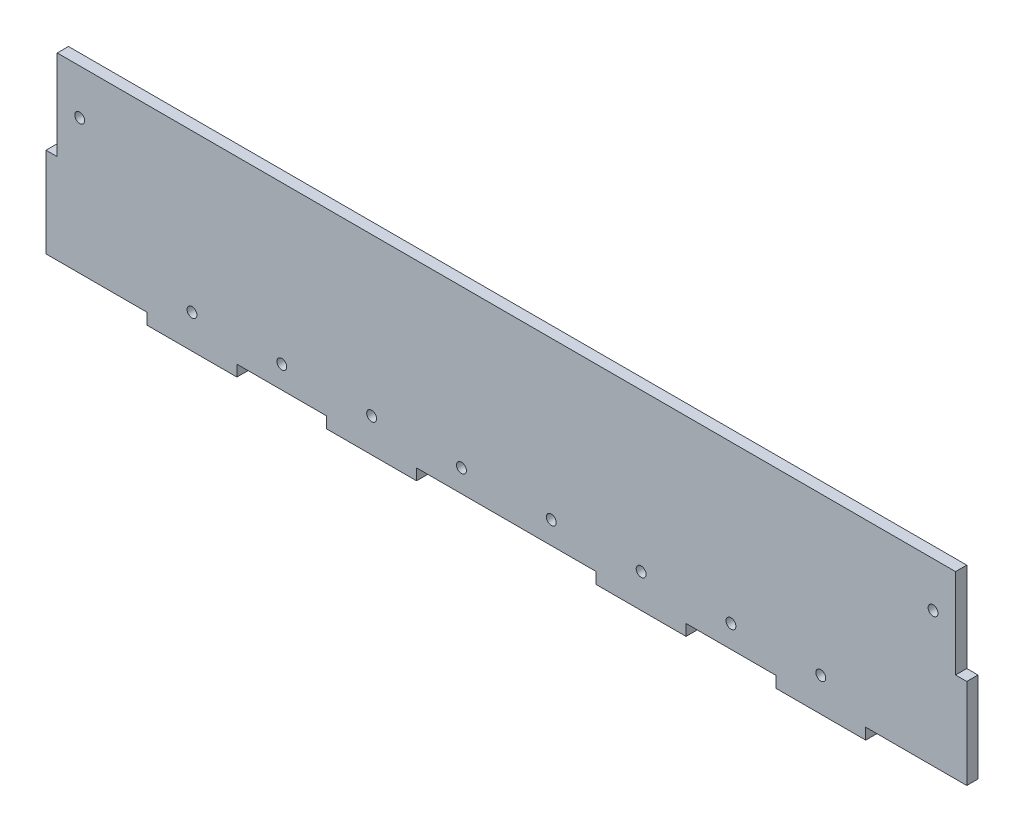
SolidWorks part; units mm, degrees
ref_plane "前视基准面" through (0, 0, 0) normal (0, 0, 1) x (1, 0, 0)
ref_plane "上视基准面" through (0, 0, 0) normal (0, 1, 0) x (1, 0, 0)
ref_plane "右视基准面" through (0, 0, 0) normal (1, 0, 0) x (0, 0, -1)
sketch "草图1" plane through (0, 0, 0) normal (0, 0, 1) x (1, 0, 0)
  line L2 (-200, 150) -> (200, 150)
  line L3 (200, -150) -> (200, -110)
  line L4 (-200, -150) -> (-200, -110)
  line L5 (-200, -150) -> (-160, -150)
  line L6 (-200, -150) -> (-160, -150)
  line L7 (-160, -150) -> (-160, -155)
  line L8 (-160, -155) -> (-120, -155)
  line L9 (-120, -155) -> (-120, -150)
  line L10 (-120, -150) -> (-80, -150)
  line L11 (-80, -150) -> (-80, -155)
  line L12 (-80, -155) -> (-40, -155)
  line L13 (-40, -155) -> (-40, -150)
  line L14 (-40, -150) -> (40, -150)
  line L15 (40, -150) -> (40, -155)
  line L16 (40, -155) -> (80, -155)
  line L17 (80, -155) -> (80, -150)
  line L18 (80, -150) -> (120, -150)
  line L19 (120, -150) -> (120, -155)
  line L20 (120, -155) -> (160, -155)
  line L21 (160, -155) -> (160, -150)
  line L22 (80, -150) -> (120, -150)
  line L23 (-120, -150) -> (-80, -150)
  line L24 (-40, -150) -> (40, -150)
  line L25 (160, -150) -> (200, -150)
  line L26 (-200, 110) -> (-200, 150)
  line L27 (-200, -70) -> (-200, -30)
  line L28 (-205, -30) -> (-205, 30)
  line L29 (-205, 30) -> (-200, 30)
  line L30 (-200, 30) -> (-200, 70)
  line L31 (-200, 70) -> (-205, 70)
  line L32 (-205, 70) -> (-205, 110)
  line L33 (-205, 110) -> (-200, 110)
  line L34 (-205, -30) -> (-200, -30)
  line L35 (-200, -70) -> (-205, -70)
  line L36 (-205, -70) -> (-205, -110)
  line L37 (-205, -110) -> (-200, -110)
  line L38 (-200, 30) -> (-200, 70)
  line L39 (200, 110) -> (200, 150)
  line L40 (205, -70) -> (205, -110)
  line L41 (205, -110) -> (200, -110)
  line L42 (200, -70) -> (205, -70)
  line L43 (205, -30) -> (200, -30)
  line L44 (205, -30) -> (205, 30)
  line L45 (205, 30) -> (200, 30)
  line L46 (200, 70) -> (205, 70)
  line L47 (205, 70) -> (205, 110)
  line L48 (205, 110) -> (200, 110)
  line L49 (200, 30) -> (200, 70)
  line L50 (200, -70) -> (200, -30)
  circle A0 centre (-140, -140) radius 2.2
  circle A1 centre (-100, -140) radius 2.2
  circle A2 centre (-60, -140) radius 2.2
  circle A3 centre (-20, -140) radius 2.2
  circle A4 centre (20, -140) radius 2.2
  circle A5 centre (60, -140) radius 2.2
  circle A6 centre (100, -140) radius 2.2
  circle A7 centre (140, -140) radius 2.2
  circle A8 centre (-190, 110) radius 2.2
  circle A9 centre (-190, 70) radius 2.2
  circle A10 centre (-190, 30) radius 2.2
  circle A11 centre (-190, -30) radius 2.2
  circle A12 centre (-190, -70) radius 2.2
  circle A13 centre (-190, -110) radius 2.2
  circle A14 centre (190, -110) radius 2.2
  circle A15 centre (190, -70) radius 2.2
  circle A16 centre (190, -30) radius 2.2
  circle A17 centre (190, 30) radius 2.2
  circle A18 centre (190, 70) radius 2.2
  circle A19 centre (190, 110) radius 2.2
extrude "凸台-拉伸1" add sketch "草图1" along normal blind 5 contours L42 L50 L43 L44 L45 L49 L46 L47 L48 L39 L2 L26 L33 L32 L31 L30 L29 L28 L34 L27 L35 L36 L37 L4 L5 L7 L8 L9 L10 L11 L12 L13 L14 L15 L16 L17 L18 L19 L20 L21 L25 L3 L41 L40 A18 A16 A14
sketch "草图2" plane through (0, 0, 5) normal (0, 0, 1) x (1, 0, 0)
  line L0 (-205, 110) -> (-200, 110)
  line L1 (-205, 110) -> (-205, -110.2824)
  line L2 (-200, 110) -> (-200, -110.2824)
  line L3 (-205, -110.2824) -> (-200, -110.2824)
  line L4 (200, 110) -> (205, 110)
  line L5 (200, 110) -> (200, -109.8687)
  line L6 (205, 110) -> (205, -109.8687)
  line L7 (200, -109.8687) -> (205, -109.8687)
extrude "切除-拉伸1" cut sketch "草图2" against normal blind 10
sketch "草图3" plane through (0, 0, 5) normal (0, 0, 1) x (1, 0, 0)
  line L0 (-200, 150) -> (-205, 150)
  line L1 (-205, 150) -> (-205, 110)
  line L2 (-205, 110) -> (-200, 110)
  line L3 (-200, -150) -> (-200, 150) construction
  line L4 (-200, 30) -> (-200, 70)
  line L5 (-200, 70) -> (-205, 70)
  line L6 (-205, 70) -> (-205, 30)
  line L7 (-205, 30) -> (-200, 30)
  line L9 (-200, -30) -> (-205, -30)
  line L10 (-205, -30) -> (-205, -70)
  line L11 (-205, -70) -> (-200, -70)
  line L13 (-200, -110) -> (-205, -110)
  line L14 (-205, -110) -> (-205, -150)
  line L15 (-205, -150) -> (-200, -150)
  line L16 (-200, -70) -> (-200, -30)
  line L19 (205, -150) -> (200, -150)
  line L20 (205, -110) -> (205, -150)
  line L21 (200, -110) -> (205, -110)
  line L23 (205, -70) -> (200, -70)
  line L24 (205, -30) -> (205, -70)
  line L25 (200, -30) -> (205, -30)
  line L27 (205, 30) -> (200, 30)
  line L28 (205, 70) -> (205, 30)
  line L29 (200, 70) -> (205, 70)
  line L31 (205, 110) -> (200, 110)
  line L32 (205, 150) -> (205, 110)
  line L33 (200, 150) -> (205, 150)
  line L34 (-200, -150) -> (-200, -110)
  line L35 (200, 150) -> (200, 110)
  line L36 (-200, 110) -> (-200, 150)
  line L37 (200, 70) -> (200, 30)
  line L38 (200, -30) -> (200, -70)
  line L39 (200, -110) -> (200, -150)
extrude "凸台-拉伸3" add sketch "草图3" against normal blind 5
sketch "草图4" plane through (0, 0, 5) normal (0, 0, 1) x (1, 0, 0)
  line L0 (-193.4037, 139.8055) -> (197.0175, 139.8055)
  line L1 (-193.4037, 139.8055) -> (-193.4037, -124.8847)
  line L2 (197.0175, 139.8055) -> (197.0175, -124.8847)
  line L3 (-193.4037, -124.8847) -> (197.0175, -124.8847)
extrude "凸台-拉伸4" add sketch "草图4" against normal blind 5
sketch "草图5" plane through (0, 0, 5) normal (0, 0, 1) x (1, 0, 0)
  circle A11 centre (-190, 90) radius 2.2
  circle A12 centre (-190, 50) radius 2.2
  circle A13 centre (-190, 0) radius 2.2
  circle A14 centre (-190, -50) radius 2.2
  circle A15 centre (-190, -90) radius 2.2
  circle A16 centre (190, -90) radius 2.2
  circle A17 centre (190, -50) radius 2.2
  circle A18 centre (190, 0) radius 2.2
  circle A19 centre (190, 50) radius 2.2
  circle A20 centre (190, 90) radius 2.2
extrude "切除-拉伸2" cut sketch "草图5" against normal blind 5
sketch "草图6" plane through (0, 0, 5) normal (0, 0, 1) x (1, 0, 0)
  line L0 (-205, -70) -> (205, -70)
  line L1 (-205, -70) -> (-205, 196.694)
  line L2 (205, -70) -> (205, 196.694)
  line L3 (-205, 196.694) -> (205, 196.694)
extrude "切除-拉伸4" cut sketch "草图6" against normal blind 10
